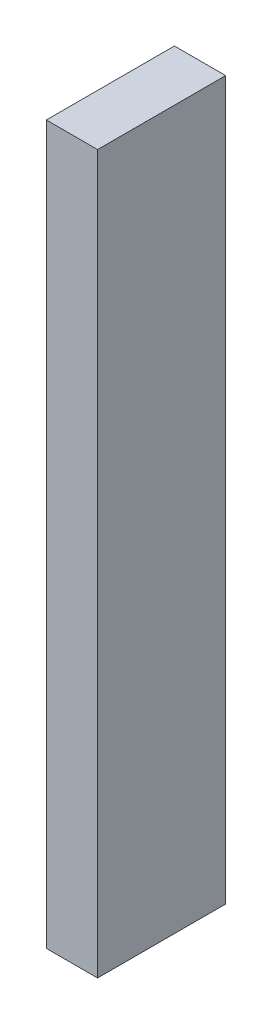
SolidWorks part; units mm, degrees
ref_plane "Front Plane" through (0, 0, 0) normal (0, 0, 1) x (1, 0, 0)
ref_plane "Top Plane" through (0, 0, 0) normal (0, 1, 0) x (1, 0, 0)
ref_plane "Right Plane" through (0, 0, 0) normal (1, 0, 0) x (0, 0, -1)
sketch "Sketch1" plane through (0, 0, 0) normal (0, 1, 0) x (1, 0, 0)
  line L1 (0, 0) -> (25.4, 0)
  line L2 (0, 0) -> (0, 63.5)
  line L3 (0, 63.5) -> (25.4, 63.5)
  line L4 (25.4, 0) -> (25.4, 63.5)
  dimension "D1" = 63.5
  dimension "D2" = 25.4
extrude "Boss-Extrude1" add sketch "Sketch1" along normal blind 355.6
